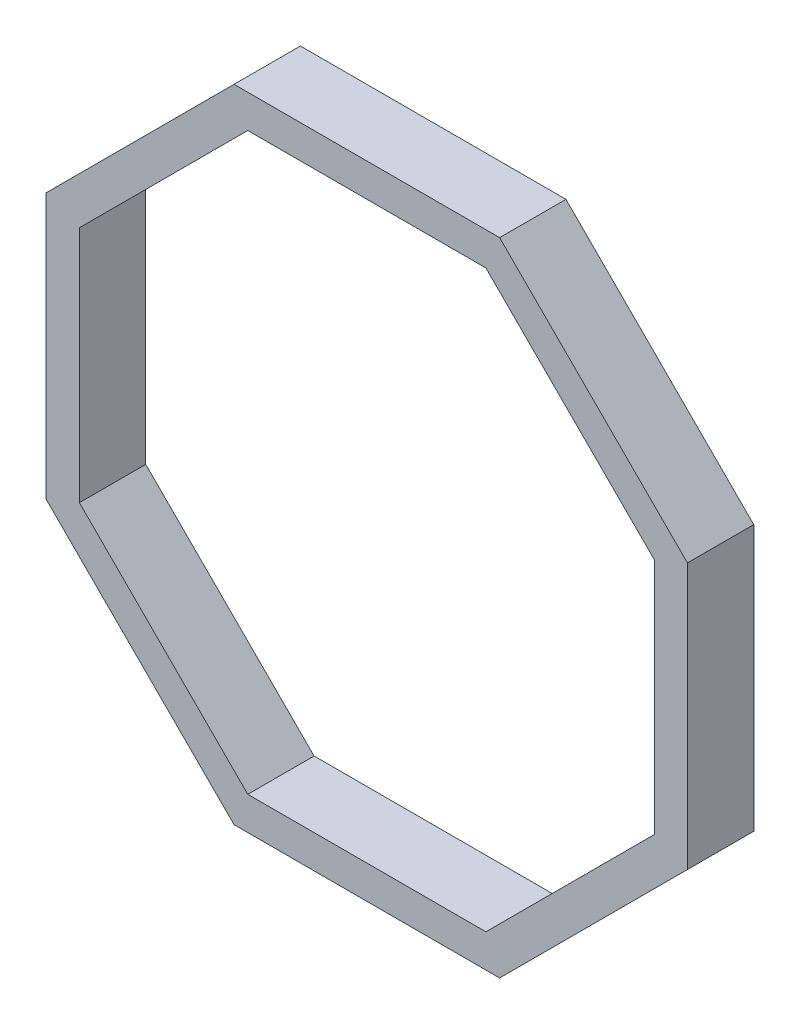
SolidWorks part; units mm, degrees
ref_plane "Plano frontal" through (0, 0, 0) normal (0, 0, 1) x (1, 0, 0)
ref_plane "Plano superior" through (0, 0, 0) normal (0, 1, 0) x (1, 0, 0)
ref_plane "Plano direito" through (0, 0, 0) normal (1, 0, 0) x (0, 0, -1)
sketch "Esboço1" plane through (0, 0, 0) normal (0, 0, 1) x (1, 0, 0)
  line L1 (145, 60.061) -> (60.061, 145)
  line L2 (60.061, 145) -> (-60.061, 145)
  line L3 (-60.061, 145) -> (-145, 60.061)
  line L4 (-145, 60.061) -> (-145, -60.061)
  line L5 (-145, -60.061) -> (-60.061, -145)
  line L6 (-60.061, -145) -> (60.061, -145)
  line L7 (60.061, -145) -> (145, -60.061)
  line L8 (145, -60.061) -> (145, 60.061)
  line L9 (130, 53.8478) -> (53.8478, 130)
  line L10 (53.8478, 130) -> (-53.8478, 130)
  line L11 (-53.8478, 130) -> (-130, 53.8478)
  line L12 (-130, 53.8478) -> (-130, -53.8478)
  line L13 (-130, -53.8478) -> (-53.8478, -130)
  line L14 (-53.8478, -130) -> (53.8478, -130)
  line L15 (53.8478, -130) -> (130, -53.8478)
  line L16 (130, -53.8478) -> (130, 53.8478)
  circle A0 centre (0, 0) radius 145 construction
  circle A1 centre (0, 0) radius 130 construction
extrude "Ressalto-extrusão1" add sketch "Esboço1" along normal blind 30
